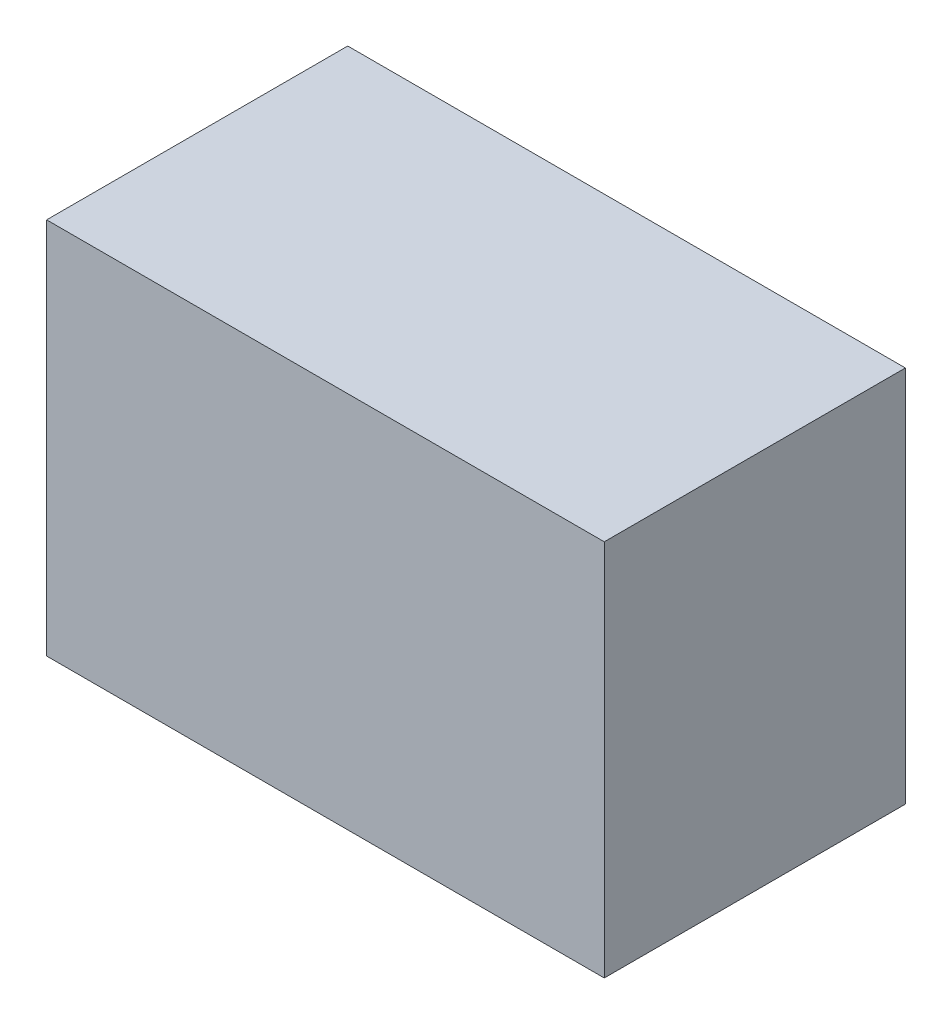
SolidWorks part; units mm, degrees
material "Water"
ref_plane "Front Plane" through (0, 0, 0) normal (0, 0, 1) x (1, 0, 0)
ref_plane "Top Plane" through (0, 0, 0) normal (0, 1, 0) x (1, 0, 0)
ref_plane "Right Plane" through (0, 0, 0) normal (1, 0, 0) x (0, 0, -1)
sketch "Sketch1" plane through (0, 0, 0) normal (0, 0, 1) x (1, 0, 0)
  line L1 (-46.3, -31.365) -> (46.3, -31.365)
  line L2 (-46.3, -31.365) -> (-46.3, 31.365)
  line L3 (-46.3, 31.365) -> (46.3, 31.365)
  line L4 (46.3, -31.365) -> (46.3, 31.365)
  line L5 (-46.3, -31.365) -> (46.3, 31.365) construction
  line L6 (-46.3, 31.365) -> (46.3, -31.365) construction
  point P0 (0, 0)
  dimension "D1" = 92.6
  dimension "D2" = 62.73
extrude "Boss-Extrude1" add sketch "Sketch1" along normal blind 50
